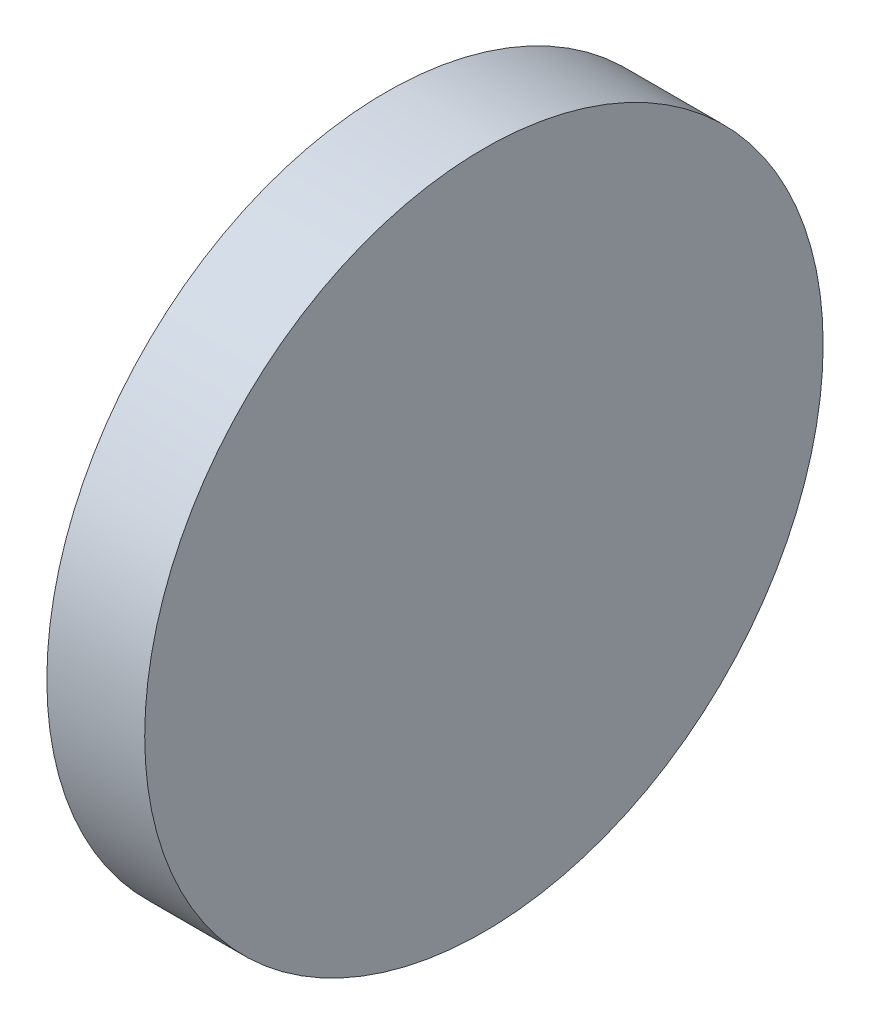
SolidWorks part; units mm, degrees
material "未指定"
ref_plane "正面" through (0, 0, 0) normal (0, 0, 1) x (1, 0, 0)
ref_plane "平面" through (0, 0, 0) normal (0, 1, 0) x (1, 0, 0)
ref_plane "右側面" through (0, 0, 0) normal (1, 0, 0) x (0, 0, -1)
sketch "ｽｹｯﾁ1" plane through (0, 0, 0) normal (0, 0, 1) x (1, 0, 0)
  line L0 (0, 0) -> (25, 0) construction
  line L1 (0, 0) -> (15, 0)
  line L2 (15, 0) -> (15, 52)
  line L3 (15, 52) -> (0, 52)
  line L4 (0, 52) -> (0, 0)
  dimension "D1" = 15
  dimension "D2" = 52
revolve "円板 切り出し" add sketch "ｽｹｯﾁ1" angle 360 about L0
equation "\"WINDOW_T\" = 15"
equation "\"D1@ｽｹｯﾁ1\" = \"WINDOW_T\""
equation "\"WINDOW_OD\" = 104"
equation "\"D2@ｽｹｯﾁ1\" = \"WINDOW_OD\" / 2"
